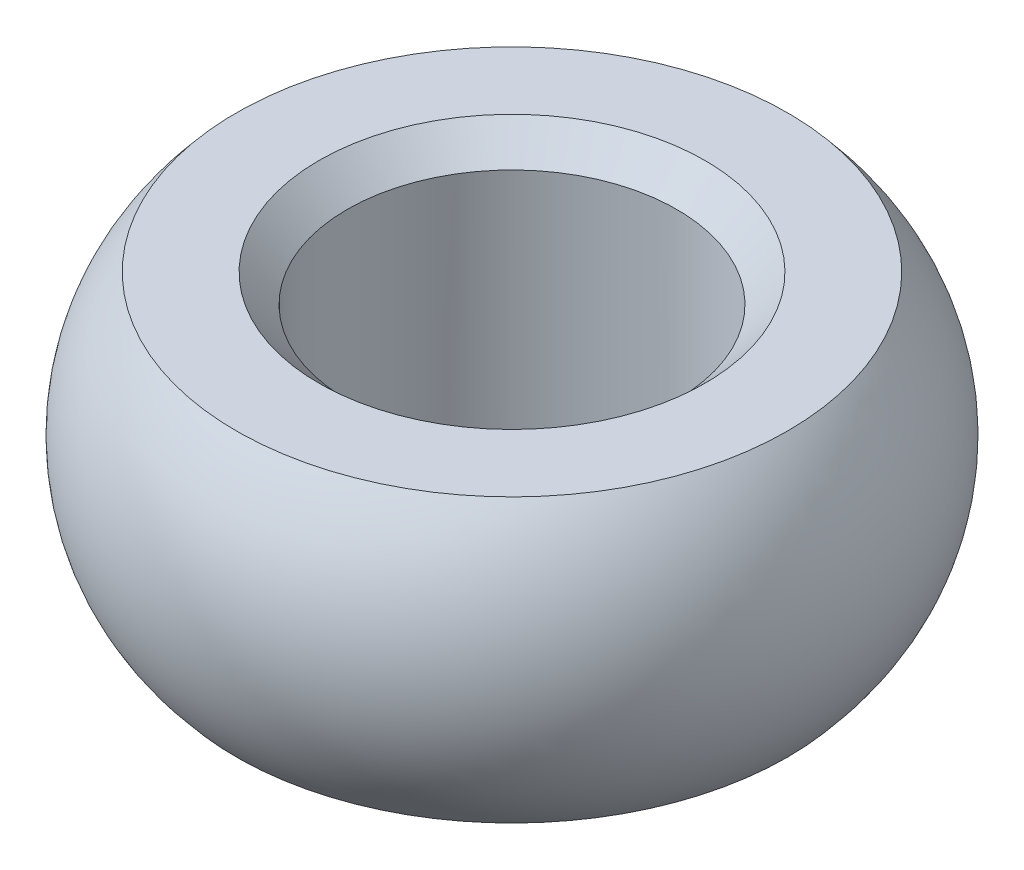
SolidWorks part; units mm, degrees
material "Custom Plastic"
ref_plane "Front Plane" through (0, 0, 0) normal (0, 0, 1) x (1, 0, 0)
ref_plane "Top Plane" through (0, 0, 0) normal (0, 1, 0) x (1, 0, 0)
ref_plane "Right Plane" through (0, 0, 0) normal (1, 0, 0) x (0, 0, -1)
sketch "Sketch1" plane through (0, 0, 0) normal (0, 0, 1) x (1, 0, 0)
  line L0 (0, -482.6299) -> (0, 23648.8631) construction
  line L1 (-482.6299, 0) -> (23648.8631, 0) construction
  line L2 (29.2705, 15) -> (17.5, 15)
  line L3 (17.5, 15) -> (17.5, -15)
  line L4 (17.5, -15) -> (29.2705, -15)
  arc A0 (29.2705, 15) -> (29.2705, -15) centre (12.5, 0) cw
  point P7 (17.5, 0)
  point P9 (35, 0)
  dimension "D3" = 22.5
  dimension "D1" = 30
  dimension "D2" = 17.5
  dimension "D4" = 70
revolve "Revolve1" add sketch "Sketch1" angle 360 about L0
chamfer "Chamfer1" distance 3 angle 45 2 edges at (17.5, 15, 0) (17.5, -15, 0)
